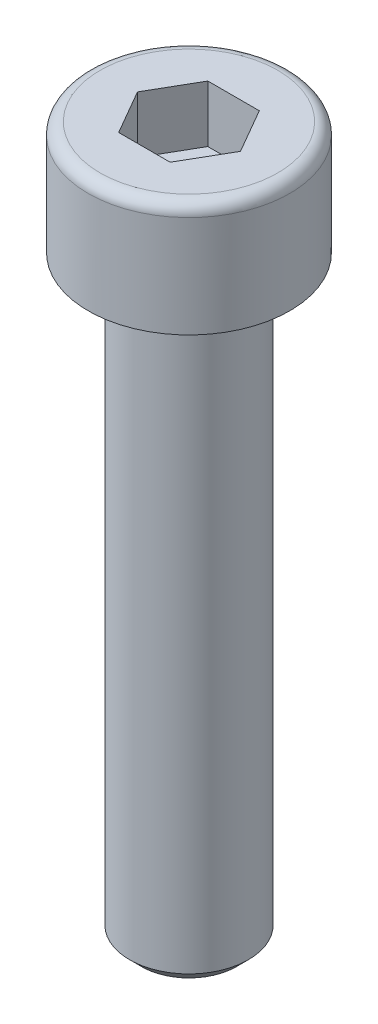
SolidWorks part; units mm, degrees
material "Cast Stainless Steel"
ref_plane "Front Plane" through (0, 0, 0) normal (0, 0, 1) x (1, 0, 0)
ref_plane "Top Plane" through (0, 0, 0) normal (0, 1, 0) x (1, 0, 0)
ref_plane "Right Plane" through (0, 0, 0) normal (1, 0, 0) x (0, 0, -1)
sketch "Sketch1" plane through (0, 0, 0) normal (0, 0, 1) x (1, 0, 0)
  line L0 (0, 0) -> (0, 3.82)
  line L1 (0, 3.82) -> (3.39, 3.82)
  line L2 (3.39, 3.82) -> (3.39, 0)
  line L3 (3.39, 0) -> (2, 0)
  line L4 (2, 0) -> (2, -20)
  line L5 (2, -20) -> (0, -20)
  line L6 (0, -20) -> (0, 0)
  line L7 (0, 3.82) -> (0, 12.7536) construction
  dimension "D1" = 20
  dimension "D2" = 3.82
  dimension "D3" = 4
  dimension "D4" = 6.78
revolve "Revolve1" add sketch "Sketch1" angle 360 about L7
chamfer "Chamfer1" distance 0.4 angle 45 1 edges at (0, -20, -2)
fillet "Fillet1" radius 0.4 1 edges at (0, 3.82, -3.39)
sketch "Sketch2" plane through (0, 3.82, 0) normal (0, 1, 0) x (1, 0, 0)
  line L1 (0.866, -1.5) -> (1.7321, 0)
  line L2 (1.7321, 0) -> (0.866, 1.5)
  line L3 (0.866, 1.5) -> (-0.866, 1.5)
  line L4 (-0.866, 1.5) -> (-1.7321, 0)
  line L5 (-1.7321, 0) -> (-0.866, -1.5)
  line L6 (-0.866, -1.5) -> (0.866, -1.5)
  circle A0 centre (0, 0) radius 1.5 construction
  dimension "D1" = 3
extrude "Cut-Extrude1" cut sketch "Sketch2" against normal blind 1.91
equation "\"d\"= 4"
equation "\"dk\"= 6.78"
equation "\"k\"= 3.82"
equation "\"s\"= 3"
equation "\"L\"= 20"
equation "\"D4@Sketch1\"=\"dk\""
equation "\"D2@Sketch1\"=\"k\""
equation "\"D1@Sketch1\"=\"L\""
equation "\"D3@Sketch1\"=\"d\""
equation "\"D1@Chamfer1\"=\"d\"/10"
equation "\"D1@Fillet1\"=\"d\"/10"
equation "\"D1@Sketch2\"=\"s\""
equation "\"D1@Cut-Extrude1\"=\"k\"/2"
